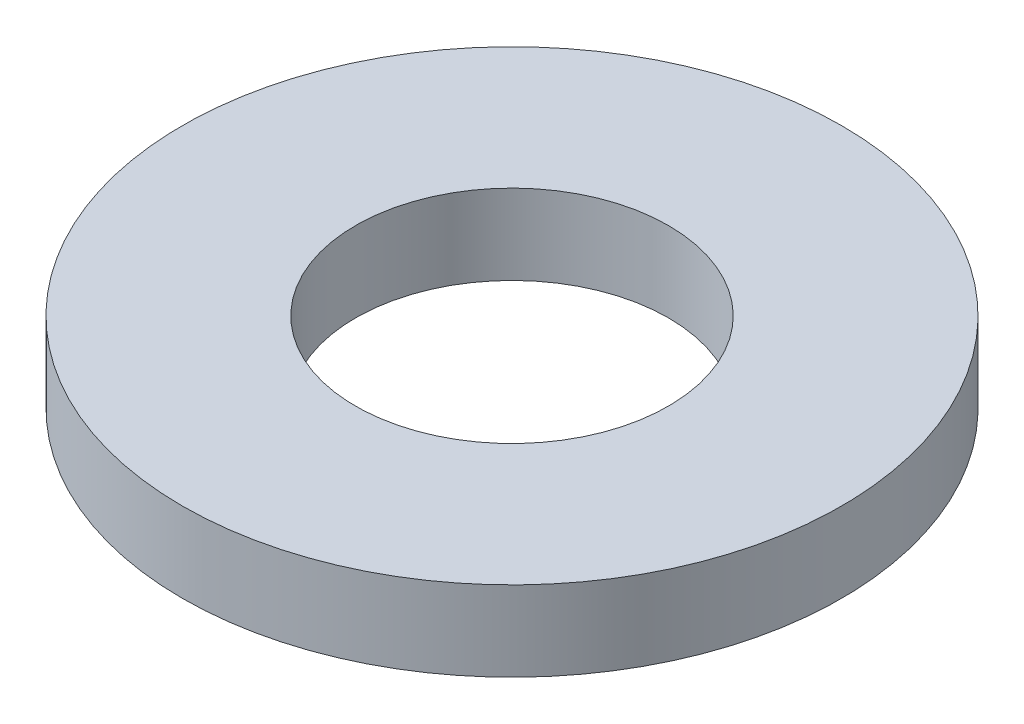
SolidWorks part; units mm, degrees
ref_plane "Front Plane" through (0, 0, 0) normal (0, 0, 1) x (1, 0, 0)
ref_plane "Top Plane" through (0, 0, 0) normal (0, 1, 0) x (1, 0, 0)
ref_plane "Right Plane" through (0, 0, 0) normal (1, 0, 0) x (0, 0, -1)
sketch "Sketch1" plane through (0, 0, 0) normal (0, 1, 0) x (1, 0, 0)
  circle A0 centre (0, 0) radius 12.36
  dimension "D1" = 24.72
extrude "Boss-Extrude1" add sketch "Sketch1" along normal blind 3
sketch "Sketch2" plane through (0, 0, 0) normal (0, -1, 0) x (-1, 0, 0)
  circle A0 centre (0, 0) radius 5.8674
  dimension "D1" = 11.7348
extrude "Cut-Extrude1" cut sketch "Sketch2" against normal through all
sketch "Sketch4" plane through (0, 3, 0) normal (0, 1, 0) x (1, 0, 0)
  circle A0 centre (0, 0) radius 12.0429 construction
  text T0 "<b>1mm</b>" font "Cambria" height 5.08
extrude "Cut-Extrude2" [suppressed] cut sketch "Sketch4" against normal blind 0.2
